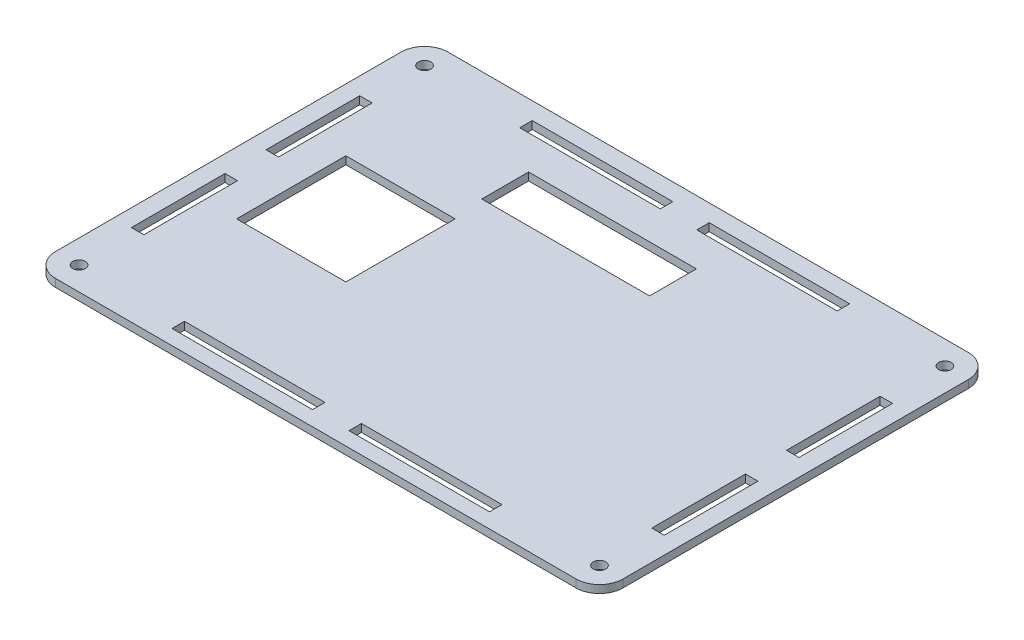
SolidWorks part; units mm, degrees
ref_plane "Front Plane" through (0, 0, 0) normal (0, 0, 1) x (1, 0, 0)
ref_plane "Top Plane" through (0, 0, 0) normal (0, 1, 0) x (1, 0, 0)
ref_plane "Right Plane" through (0, 0, 0) normal (1, 0, 0) x (0, 0, -1)
sketch "Sketch1" plane through (0, 0, 0) normal (0, 1, 0) x (1, 0, 0)
  line L0 (0, 8.1414) -> (0, -124047.6473) construction
  line L1 (0, 0) -> (145.34, 0)
  line L2 (0, 0) -> (0, 100.51)
  line L3 (0, 100.51) -> (145.34, 100.51)
  line L4 (145.34, 0) -> (145.34, 100.51)
  line L9 (3.753, 0) -> (124059.5417, 0) construction
  line L10 (12, 0) -> (12, -50000) construction
  line L11 (133.34, 0) -> (133.34, -50000) construction
  line L12 (0, 12) -> (-50000, 12) construction
  line L13 (-45.6158, 88.51) -> (49954.3842, 88.51) construction
  line L14 (-2.2542, 48) -> (-50002.2542, 48) construction
  line L15 (-71.6312, 38) -> (49928.3688, 38) construction
  line L16 (89.34, 114.3993) -> (89.34, -49885.6007) construction
  line L17 (60, 108.3918) -> (60, -49891.6082) construction
  line L18 (99.34, 117.8875) -> (99.34, -49882.1125) construction
  line L19 (32, 7.0141) -> (68, 7.0141)
  line L20 (32, 96.11) -> (68, 96.11)
  line L21 (32, 96.11) -> (32, 92.91)
  line L22 (32, 92.91) -> (68, 92.91)
  line L23 (68, 96.11) -> (68, 92.91)
  line L24 (113.34, 96.11) -> (77.34, 96.11)
  line L25 (113.34, 96.11) -> (113.34, 92.91)
  line L26 (113.34, 92.91) -> (77.34, 92.91)
  line L27 (77.34, 96.11) -> (77.34, 92.91)
  line L28 (32, 7.0141) -> (32, 3.8141)
  line L29 (32, 3.8141) -> (68, 3.8141)
  line L30 (68, 7.0141) -> (68, 3.8141)
  line L31 (113.34, 7.0141) -> (77.34, 7.0141)
  line L32 (113.34, 7.0141) -> (113.34, 3.8141)
  line L33 (113.34, 3.8141) -> (77.34, 3.8141)
  line L34 (77.34, 7.0141) -> (77.34, 3.8141)
  line L40 (4.4, 79.51) -> (7.6, 79.51)
  line L41 (4.4, 79.51) -> (4.4, 55.51)
  line L42 (4.4, 55.51) -> (7.6, 55.51)
  line L43 (7.6, 79.51) -> (7.6, 55.51)
  line L44 (4.4, 45) -> (7.6, 45)
  line L45 (4.4, 45) -> (4.4, 21)
  line L46 (4.4, 21) -> (7.6, 21)
  line L47 (7.6, 45) -> (7.6, 21)
  line L48 (137.74, 79.51) -> (140.94, 79.51)
  line L49 (137.74, 79.51) -> (137.74, 55.51)
  line L50 (137.74, 55.51) -> (140.94, 55.51)
  line L51 (140.94, 79.51) -> (140.94, 55.51)
  line L52 (137.74, 45) -> (140.94, 45)
  line L53 (137.74, 45) -> (137.74, 21)
  line L54 (137.74, 21) -> (140.94, 21)
  line L55 (140.94, 45) -> (140.94, 21)
  line L60 (15.946, 64.413) -> (43.946, 64.413)
  line L61 (15.946, 64.413) -> (15.946, 36.413)
  line L62 (15.946, 36.413) -> (43.946, 36.413)
  line L63 (43.946, 64.413) -> (43.946, 36.413)
  line L64 (85.952, 84.224) -> (42.952, 84.224)
  line L65 (85.952, 84.224) -> (85.952, 72.224)
  line L66 (85.952, 72.224) -> (42.952, 72.224)
  line L67 (42.952, 84.224) -> (42.952, 72.224)
  circle A7 centre (6, 94.51) radius 1.6
  circle A8 centre (139.34, 94.51) radius 1.6
  circle A9 centre (139.34, 6) radius 1.6
  circle A10 centre (6, 6) radius 1.6
  dimension "D14" = 10.51
  dimension "D16" = 36.097
  dimension "D22" = 6
  dimension "D24" = 6
  dimension "D26" = 6
  dimension "D28" = 6
  dimension "D1" = 100.51
  dimension "D2" = 145.34
  dimension "D3" = 12
  dimension "D4" = 12
  dimension "D5" = 12
  dimension "D6" = 12
  dimension "D7" = 40.51
  dimension "D8" = 10
  dimension "D9" = 26
  dimension "D10" = 29.34
  dimension "D11" = 48
  dimension "D12" = 10
  dimension "D13" = 34
  dimension "D15" = 15.946
  dimension "D17" = 28
  dimension "D18" = 42.952
  dimension "D19" = 43
  dimension "D20" = 12
  dimension "D21" = 16.286
  dimension "D23" = 6
  dimension "D25" = 6
  dimension "D27" = 6
  dimension "D29" = 6
  dimension "D30" = 36
  dimension "D31" = 20
  dimension "D32" = 3.2
  dimension "D33" = 36
  dimension "D34" = 20
  dimension "D35" = 20
  dimension "D36" = 3.2
  dimension "D37" = 20
  dimension "D38" = 36
  dimension "D39" = 36
  dimension "D40" = 24
  dimension "D41" = 9
  dimension "D42" = 9
  dimension "D43" = 24
  dimension "D44" = 24
  dimension "D45" = 24
  dimension "D46" = 9
  dimension "D47" = 9
  dimension "D51" = 28
extrude "Boss-Extrude1" add sketch "Sketch1" along normal blind 2
fillet "Fillet1" radius 6 1 edges at (0, 1, -100.51)
fillet "Fillet2" radius 6 1 edges at (0, 1, 0)
fillet "Fillet3" radius 6 2 edges at (145.34, 1, -100.51) (145.34, 1, 0)
